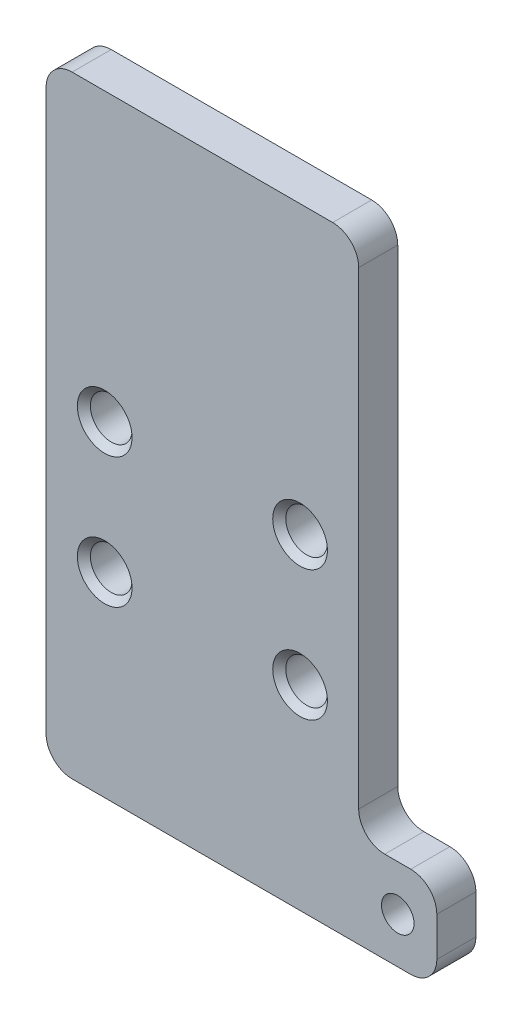
SolidWorks part; units mm, degrees
ref_plane "前视基准面" through (0, 0, 0) normal (0, 0, 1) x (1, 0, 0)
ref_plane "上视基准面" through (0, 0, 0) normal (0, 1, 0) x (1, 0, 0)
ref_plane "右视基准面" through (0, 0, 0) normal (1, 0, 0) x (0, 0, -1)
sketch "草图1" plane through (0, 0, 0) normal (0, 0, 1) x (1, 0, 0)
  line L0 (12, -25) -> (18, -25)
  line L1 (-12, 15) -> (12, 15)
  line L2 (-12, 15) -> (-12, -32)
  line L3 (-12, -32) -> (18, -32)
  line L5 (18, -25) -> (18, -32)
  line L7 (12, 15) -> (12, -25)
  circle A0 centre (-7.5, -7) radius 1.6
  circle A1 centre (7.5, -7) radius 1.6
  circle A2 centre (-7.5, -17) radius 1.6
  circle A3 centre (7.5, -17) radius 1.6
  circle A4 centre (15, -28.5) radius 1.25
  point P3 (18, -28.5)
  dimension "D6" = 3.2
  dimension "D7" = 3.2
  dimension "D9" = 3.2
  dimension "D11" = 3.2
  dimension "D16" = 2.5
  dimension "D2" = 47
  dimension "D3" = 12
  dimension "D4" = 15
  dimension "D5" = 7.5
  dimension "D8" = 7.5
  dimension "D10" = 10
  dimension "D12" = 22
  dimension "D13" = 24
  dimension "D14" = 7
  dimension "D15" = 6
  dimension "D17" = 3
extrude "凸台-拉伸1" add sketch "草图1" along normal blind 3
chamfer "倒角1" distance 0.5 angle 45 5 edges at (9.1, -17, 3) (-5.9, -17, 3) (9.1, -7, 3) (-5.9, -7, 3) (16.25, -28.5, 0)
fillet "圆角1" radius 2 6 edges at (12, 15, 1.5) (-12, 15, 1.5) (-12, -32, 1.5) (18, -32, 1.5) (18, -25, 1.5) (12, -25, 1.5)
